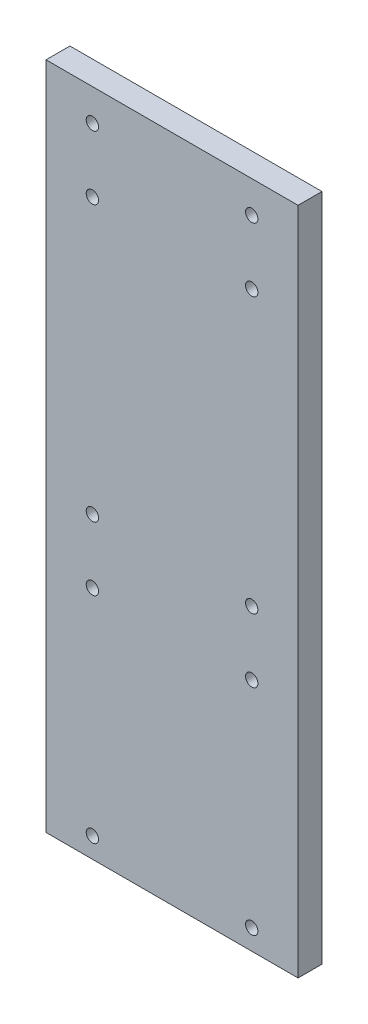
SolidWorks part; units mm, degrees
ref_plane "Płaszczyzna przednia" through (0, 0, 0) normal (0, 0, 1) x (1, 0, 0)
ref_plane "Płaszczyzna górna" through (0, 0, 0) normal (0, 1, 0) x (1, 0, 0)
ref_plane "Płaszczyzna prawa" through (0, 0, 0) normal (1, 0, 0) x (0, 0, -1)
sketch "Szkic1" plane through (0, 0, 0) normal (0, 0, 1) x (1, 0, 0)
  line L1 (1151.498, -961.9222) -> (1151.498, -793.9222)
  line L2 (1214.768, -961.9222) -> (1214.768, -793.9222)
  line L3 (1151.498, -793.9222) -> (1214.768, -793.9222)
  line L7 (1151.498, -961.9222) -> (1214.768, -961.9222)
  dimension "D1" = 63.27
  dimension "D2" = 168
extrude "Dodanie-wyciągnięcie1" add sketch "Szkic1" along normal blind 6
sketch "Szkic3" plane through (0, 0, 6) normal (0, 0, 1) x (1, 0, 0)
  line L0 (1201.583, -804.9222) -> (1201.583, -798.9222) construction
  line L1 (1204.683, -804.9222) -> (1204.683, -798.9222) construction
  line L2 (1164.683, -804.9222) -> (1164.683, -798.9222) construction
  line L3 (1161.583, -804.9222) -> (1161.583, -798.9222) construction
  line L4 (1164.683, -889.9222) -> (1164.683, -883.9222) construction
  line L5 (1161.583, -889.9222) -> (1161.583, -883.9222) construction
  line L6 (1204.683, -889.9222) -> (1204.683, -883.9222) construction
  line L7 (1201.583, -889.9222) -> (1201.583, -883.9222) construction
  line L8 (1201.583, -804.9222) -> (1201.583, -798.9222)
  line L9 (1204.683, -804.9222) -> (1204.683, -798.9222)
  line L10 (1164.683, -804.9222) -> (1164.683, -798.9222)
  line L11 (1161.583, -804.9222) -> (1161.583, -798.9222)
  line L12 (1164.683, -889.9222) -> (1164.683, -883.9222)
  line L13 (1161.583, -889.9222) -> (1161.583, -883.9222)
  line L14 (1204.683, -889.9222) -> (1204.683, -883.9222)
  line L15 (1201.583, -889.9222) -> (1201.583, -883.9222)
  line L16 (1204.683, -801.9222) -> (1201.583, -801.9222)
  line L17 (1164.683, -801.9222) -> (1161.583, -801.9222)
  line L18 (1204.683, -886.9222) -> (1201.583, -886.9222)
  line L19 (1164.683, -886.9222) -> (1161.583, -886.9222)
  line L20 (1161.583, -961.8222) -> (1161.583, -951.8222) construction
  line L21 (1164.683, -961.8222) -> (1164.683, -951.8222) construction
  line L22 (1201.583, -961.8222) -> (1201.583, -951.8222) construction
  line L23 (1204.683, -961.8222) -> (1204.683, -951.8222) construction
  line L24 (1161.583, -961.8222) -> (1161.583, -951.8222)
  line L25 (1164.683, -961.8222) -> (1164.683, -951.8222)
  line L26 (1201.583, -961.8222) -> (1201.583, -951.8222)
  line L27 (1204.683, -961.8222) -> (1204.683, -951.8222)
  line L28 (1204.683, -956.8222) -> (1201.583, -956.8222)
  line L29 (1164.683, -956.8222) -> (1161.583, -956.8222)
  circle A0 centre (1163.133, -886.9222) radius 1.55
  circle A1 centre (1203.133, -886.9222) radius 1.55
  circle A2 centre (1163.133, -801.9222) radius 1.55
  circle A3 centre (1203.133, -801.9222) radius 1.55
  circle A4 centre (1203.133, -956.8222) radius 1.55
  circle A5 centre (1163.133, -956.8222) radius 1.55
  dimension "D1" = 3.1
  dimension "D2" = 3.1
  dimension "D3" = 3.1
  dimension "D4" = 3.1
  dimension "D5" = 3.1
  dimension "D6" = 3.1
sketch "Szkic5" plane through (0, 0, 6) normal (0, 0, 1) x (1, 0, 0)
  circle A0 centre (1203.133, -956.8222) radius 1.55 construction
  circle A1 centre (1163.133, -956.8222) radius 1.55 construction
  circle A2 centre (1163.133, -886.9222) radius 1.55 construction
  circle A3 centre (1203.133, -886.9222) radius 1.55 construction
  circle A4 centre (1203.133, -801.9222) radius 1.55 construction
  circle A5 centre (1163.133, -801.9222) radius 1.55 construction
  circle A6 centre (1203.133, -956.8222) radius 1.55
  circle A7 centre (1163.133, -956.8222) radius 1.55
  circle A8 centre (1163.133, -886.9222) radius 1.55
  circle A9 centre (1203.133, -886.9222) radius 1.55
  circle A10 centre (1203.133, -801.9222) radius 1.55
  circle A11 centre (1163.133, -801.9222) radius 1.55
extrude "Wytnij-wyciągnięcie1" cut sketch "Szkic5" against normal blind 6
pattern_linear "Szyk liniowy1" count 2 spacing 16 along (0, -1, 0) of "Wytnij-wyciągnięcie1"
equation "\"tolerancja_wpusy\"=0.2"
equation "\"dlugosc_wpustu_duzy\"=20"
equation "\"srednica_otworu_M3\"=3.1"
equation "\"szerokosc_nogi_T\"=3.1"
equation "\"dlugosc_T_30\"=11"
equation "\"grubosc_na_nakretke_kwadrat\"=2"
equation "\"szerokosc_na_nakretke_kwadrat\"=5.85"
equation "\"wyokosc_nadstawki_T\"=0.5"
equation "\"dlugosc_T_20_6\"=14"
equation "\"D1@Szkic3\"=\"srednica_otworu_M3\""
equation "\"D2@Szkic3\"=\"srednica_otworu_M3\""
equation "\"D3@Szkic3\"=\"srednica_otworu_M3\""
equation "\"D4@Szkic3\"=\"srednica_otworu_M3\""
equation "\"D5@Szkic3\"=\"srednica_otworu_M3\""
equation "\"D6@Szkic3\"=\"srednica_otworu_M3\""
